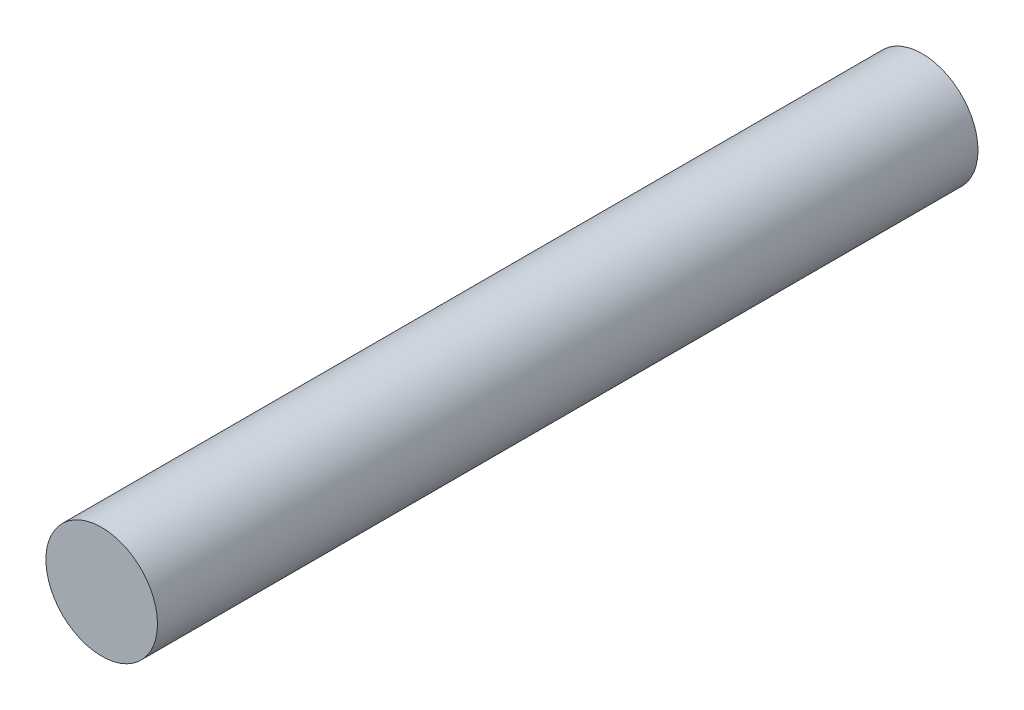
SolidWorks part; units mm, degrees
ref_plane "Piano frontale" through (0, 0, 0) normal (0, 0, 1) x (1, 0, 0)
ref_plane "Piano superiore" through (0, 0, 0) normal (0, 1, 0) x (1, 0, 0)
ref_plane "Piano destro" through (0, 0, 0) normal (1, 0, 0) x (0, 0, -1)
sketch "Schizzo1" plane through (0, 0, 0) normal (0, 0, 1) x (1, 0, 0)
  circle A0 centre (-9.7347, -1.0504) radius 1.7
  dimension "D1" = 3.4
extrude "Estrusione-Estrusione1" add sketch "Schizzo1" along normal blind 25
